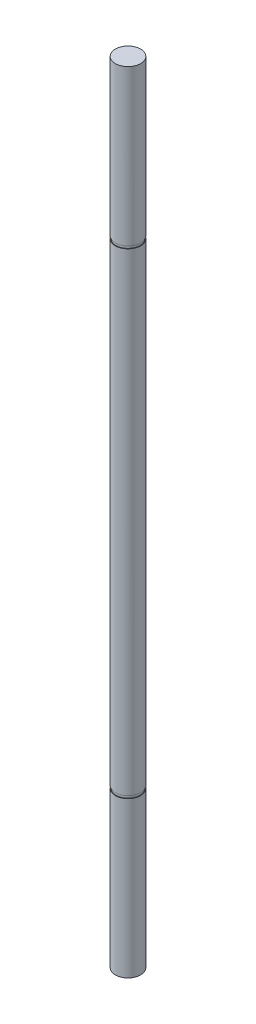
SolidWorks part; units mm, degrees
ref_plane "前视" through (0, 0, 0) normal (0, 0, 1) x (1, 0, 0)
ref_plane "上视" through (0, 0, 0) normal (0, 1, 0) x (1, 0, 0)
ref_plane "右视" through (0, 0, 0) normal (1, 0, 0) x (0, 0, -1)
sketch "草图1" plane through (0, 0, 0) normal (0, 1, 0) x (1, 0, 0)
  circle A0 centre (0, 0) radius 4
  dimension "D1" = 8
extrude "凸台-拉伸1" add sketch "草图1" along normal mid plane 250
sketch "草图3" plane through (0, 0, 0) normal (1, 0, 0) x (0, 0, -1)
  line L0 (0, 125) -> (0, -125) construction
  line L1 (3.8, 75.8) -> (8.8, 75.8)
  line L2 (3.8, 75.8) -> (3.8, 75)
  line L3 (3.8, 75) -> (8.8, 75)
  line L4 (8.8, 75.8) -> (8.8, 75)
  line L5 (3.8, 75.8) -> (8.8, 75) construction
  line L6 (3.8, 75) -> (8.8, 75.8) construction
  point P0 (6.3, 75.4)
  dimension "D1" = 75
  dimension "D2" = 0.8
  dimension "D3" = 3.8
  dimension "D4" = 5
revolve "切除-旋转1" cut sketch "草图3" angle 360 about axis through (0, 125, 0) along (0, -1, 0)
ref_plane "基准面1" through (0, 0, 0) normal (0, 1, 0) x (1, 0, 0)
mirror "镜向1" about plane through (0, 0, 0) normal (0, 1, 0) of "切除-旋转1"
